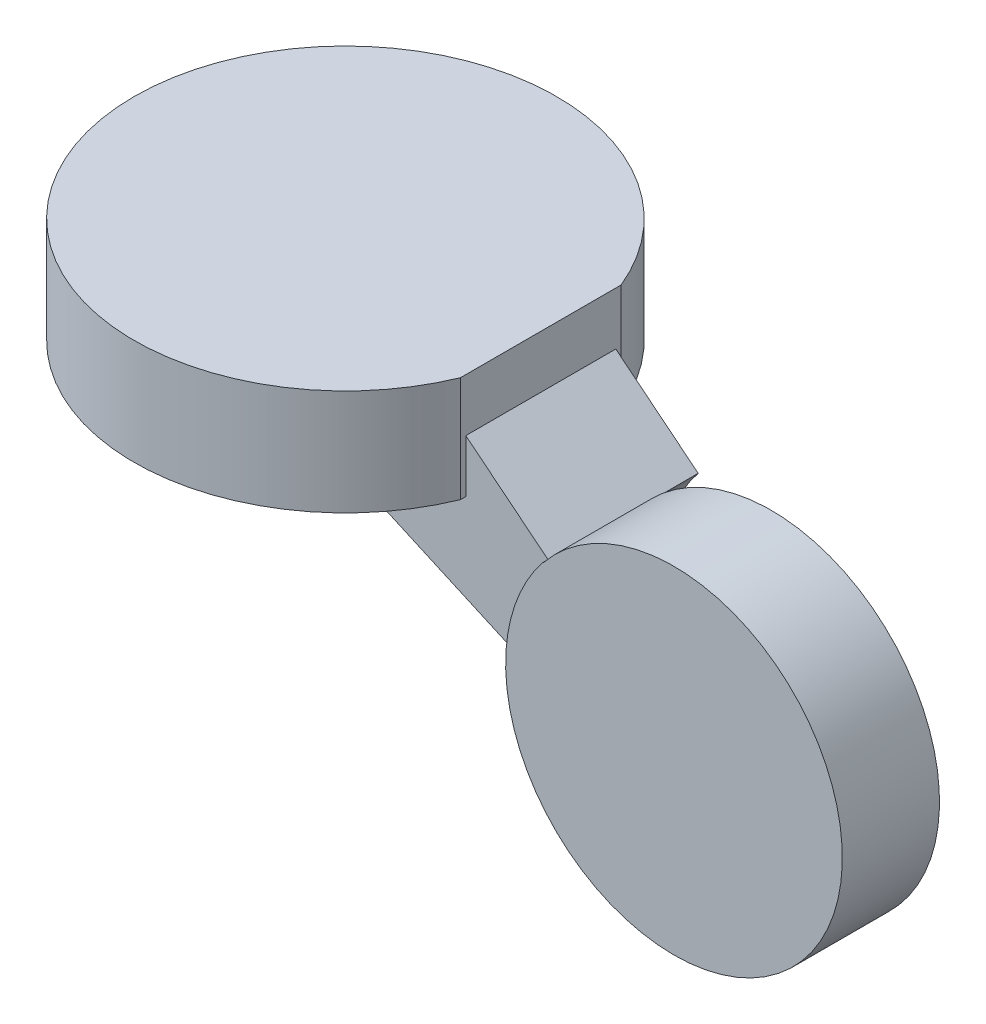
SolidWorks part; units mm, degrees
ref_plane "Front Plane" through (0, 0, 0) normal (0, 0, 1) x (1, 0, 0)
ref_plane "Top Plane" through (0, 0, 0) normal (0, 1, 0) x (1, 0, 0)
ref_plane "Right Plane" through (0, 0, 0) normal (1, 0, 0) x (0, 0, -1)
sketch "Sketch1" plane through (0, 0, 0) normal (0, 1, 0) x (1, 0, 0)
  circle A0 centre (0, 0) radius 200
extrude "Boss-Extrude1" add sketch "Sketch1" along normal blind 100 contours A0
sketch "Sketch2" plane through (0, 100, 0) normal (0, 1, 0) x (1, 0, 0)
  line L2 (185, 0) -> (185, 120.6425)
  line L3 (200, 0) -> (200, -137.8499)
  line L4 (200, -137.8499) -> (185, -137.8499)
  line L5 (185, -137.8499) -> (185, 0)
  line L6 (185, 120.6425) -> (192.5, 120.6425)
  line L7 (200, 0) -> (200, 120.6425)
  line L8 (200, 120.6425) -> (185, 120.6425)
  circle A0 centre (0, 0) radius 200 construction
  circle M1 centre (0, 0) radius 200
extrude "Cut-Extrude2" cut sketch "Sketch2" against normal blind 100 contours L5 L2 M1
sketch "Sketch4" plane through (0, 0, 0) normal (0, 0, 1) x (1, 0, 0)
  line L0 (185, 50) -> (185, 0)
  line L1 (387.0757, -112.9664) -> (251.9246, -112.9664)
  line L2 (251.9246, -112.9664) -> (0, 0)
  line L3 (185, 50) -> (387.0757, -112.9664)
  line L4 (185, 0) -> (185, 100) construction
  line L5 (185, 0) -> (0, 0)
  point P0 (387.0757, -112.9664)
extrude "Boss-Extrude2" add sketch "Sketch4" against normal up to vertex (75.9934 mm away)
sketch "Sketch7" plane through (0, 0, 0) normal (0, 0, 1) x (1, 0, 0)
  line L0 (0, 0) -> (185, 0)
  line L1 (185, 0) -> (185, 50)
  line L2 (185, 50) -> (387.0757, -112.9664)
  line L3 (387.0757, -112.9664) -> (251.9246, -112.9664)
  line L4 (251.9246, -112.9664) -> (0, 0)
extrude "Boss-Extrude3" add sketch "Sketch7" along normal up to vertex (75.9934 mm away)
sketch "Sketch9" plane through (0, 0, 75.9934) normal (0, 0, 1) x (1, 0, 0)
  circle A0 centre (387.0757, -112.9664) radius 159.375
extrude "Boss-Extrude4" add sketch "Sketch9" against normal up to vertex (151.9868 mm away) contours A0
sketch "Sketch11" plane through (0, 0, -75.9934) normal (0, 0, -1) x (-1, 0, 0)
  circle A1 centre (-387.0757, -112.9664) radius 159.375
extrude "Cut-Extrude3" cut sketch "Sketch11" against normal blind 60 contours A1
sketch "Sketch12" plane through (0, 0, 75.9934) normal (0, 0, 1) x (1, 0, 0)
  line L0 (0, 0) -> (228.0604, -102.2654)
  line L1 (0, 0) -> (185, 0)
  line L2 (185, 0) -> (185, 50)
  line L3 (185, 50) -> (263.0168, -12.9176)
  arc A1 (262.7709, -12.7193) -> (228.0604, -102.2654) centre (388.8324, -113.0847) ccw
  line M4 (185, 50) -> (185, 0)
  line M5 (185, 0) -> (0, 0)
  line M6 (0, 0) -> (228.0604, -102.2654)
extrude "Cut-Extrude4" cut sketch "Sketch12" against normal blind 5 contours A1 L3 M4 M5 M6
sketch "Sketch14" plane through (0, 0, -75.9934) normal (0, 0, -1) x (-1, 0, 0)
  line L0 (-228.0604, -102.2654) -> (0, 0)
  line L1 (0, 0) -> (-185, 0)
  line L2 (-185, 0) -> (-185, 50)
  line L3 (-185, 50) -> (-263.0168, -12.9176)
  arc A0 (-263.0168, -12.9176) -> (-228.0604, -102.2654) centre (-387.0757, -112.9664) cw
extrude "Cut-Extrude5" cut sketch "Sketch14" against normal blind 5
